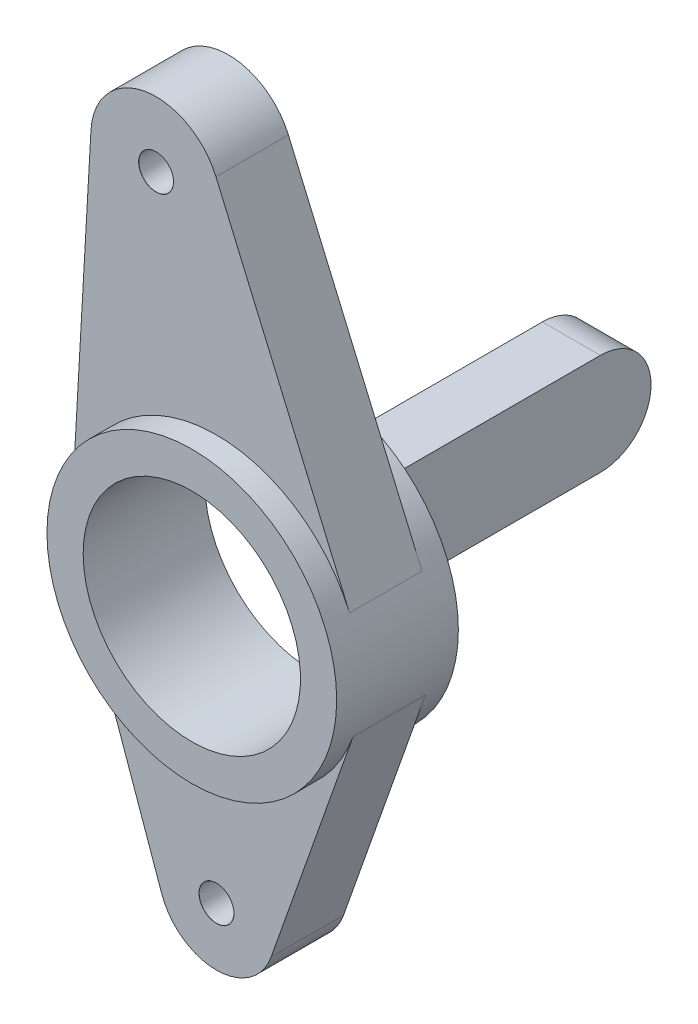
SolidWorks part; units mm, degrees
ref_plane "Ön Düzlem" through (0, 0, 0) normal (0, 0, 1) x (1, 0, 0)
ref_plane "Üst Düzlem" through (0, 0, 0) normal (0, 1, 0) x (1, 0, 0)
ref_plane "Sağ Düzlem" through (0, 0, 0) normal (1, 0, 0) x (0, 0, -1)
sketch "Çizim1" plane through (0, 0, 0) normal (0, 0, 1) x (1, 0, 0)
  circle A0 centre (0, 0) radius 50
  circle A1 centre (0, 0) radius 37.5
  dimension "D1" = 100
  dimension "D2" = 75
extrude "Yükseklik-Ekstrüzyon1" add sketch "Çizim1" along normal mid plane 42
sketch "Çizim2" plane through (0, 0, 0) normal (0, 0, 1) x (1, 0, 0)
  line L0 (0, 0) -> (-20.8378, 118.1769) construction
  line L1 (0, 0) -> (0, -90) construction
  line L2 (-43.3016, 119.4517) -> (-49.9197, 2.8329)
  line L3 (-0.1647, 127.058) -> (45.9402, 19.7356)
  line L4 (-18.8562, -96.6667) -> (-47.1405, -16.6667)
  line L5 (18.8562, -96.6667) -> (47.1405, -16.6667)
  arc A0 (-0.1647, 127.058) -> (-43.3016, 119.4517) centre (-20.8378, 118.1769) ccw
  arc A1 (-18.8562, -96.6667) -> (18.8562, -96.6667) centre (0, -90) ccw
  circle A2 centre (0, 0) radius 50 construction
  arc A3 (47.1405, -16.6667) -> (45.9402, 19.7356) centre (0, 0) ccw
  circle A4 centre (0, 0) radius 50
  arc A5 (-49.9197, 2.8329) -> (-47.1405, -16.6667) centre (0, 0) ccw
  point P14 (47.1405, -16.6667)
  dimension "D4" = 40
  dimension "D5" = 45
  dimension "D1" = 170
  dimension "D2" = 90
  dimension "D3" = 120
  dimension "D6" = 0
extrude "Yükseklik-Ekstrüzyon2" add sketch "Çizim2" along normal mid plane 25
sketch "Çizim3" plane through (0, 0, 0) normal (1, 0, 0) x (0, 0, -1)
  line L0 (0, 0) -> (110, 0) construction
  line L1 (110, -17.5) -> (5.0694, -17.5)
  line L3 (110, 17.5) -> (5.0694, 17.5)
  line L5 (5.0694, 17.5) -> (5.0694, -17.5)
  arc A0 (110, -17.5) -> (110, 17.5) centre (110, 0) ccw
  dimension "D2" = 35
  dimension "D1" = 110
extrude "Yükseklik-Ekstrüzyon6" add sketch "Çizim3" along normal mid plane 20
hole_wizard "Ø12.0 (12) Çap Delik2" positions "3B Çizim2" profile "Çizim5" hole size "Ø12.0" standard "ANSI Metric" end condition through all
sketch3d "3B Çizim2"
  line L0 (-20.8378, 118.1769, 12.5) -> (-20.8378, 118.1769, -12.5) construction
  line L1 (0, -90, 12.5) -> (0, -90, -12.5) construction
  point P0 (-20.8378, 118.1769, 12.5)
  point P4 (0, -90, 12.5)
sketch "Çizim5" plane through (-20.8378, 118.1769, 12.5) normal (1, 0, 0) x (0, -1, 0)
  line L0 (0, 0) -> (0, 140)
  line L1 (0, 140) -> (6, 140)
  line L2 (6, 140) -> (6, 0.0241)
  line L3 (6, 0.0241) -> (6.025, 0)
  line L5 (6.025, 0) -> (0, 0)
  line L6 (-6, 0.0241) -> (-6.025, 0) construction
  line L11 (0, -6.35) -> (0, 107.95) construction
  dimension "Thru Hole Dia." = 12
  dimension "Thru Hole Depth" = 140
  dimension "Near C'Sink Dia." = 12.05
  dimension "Near C'Sink Angle" = 92
hole_wizard "Ø10.0 (10) Çap Delik1" positions "3B Çizim5" profile "Çizim7" hole size "Ø10.0" standard "ANSI Metric" end condition through all
sketch3d "3B Çizim5"
  line L0 (0, 0, 21) -> (0, 0, -21) construction
  point P0 (0, 0, 21)
sketch "Çizim7" plane through (0, 0, 21) normal (1, 0, 0) x (0, -1, 0)
  line L0 (0, 0) -> (0, 148.5)
  line L1 (0, 148.5) -> (5, 148.5)
  line L2 (5, 148.5) -> (5, 0.0241)
  line L3 (5, 0.0241) -> (5.025, 0)
  line L5 (5.025, 0) -> (0, 0)
  line L6 (-5, 0.0241) -> (-5.025, 0) construction
  line L11 (0, -6.35) -> (0, 107.95) construction
  dimension "Thru Hole Dia." = 10
  dimension "Thru Hole Depth" = 148.5
  dimension "Near C'Sink Dia." = 10.05
  dimension "Near C'Sink Angle" = 92
sketch "Çizim8" plane through (0, 0, 0) normal (0, 0, 1) x (1, 0, 0)
  circle A0 centre (0, 0) radius 37.5
extrude "Kes-Ekstrüzyon2" cut sketch "Çizim8" against normal blind 21 and the other way through all
sketch "Çizim9" plane through (0, 0, 0) normal (0, 0, 1) x (1, 0, 0)
  circle A0 centre (0, 0) radius 37.5
extrude "Kes-Ekstrüzyon4" cut sketch "Çizim9" against normal blind 22 and the other way through all
